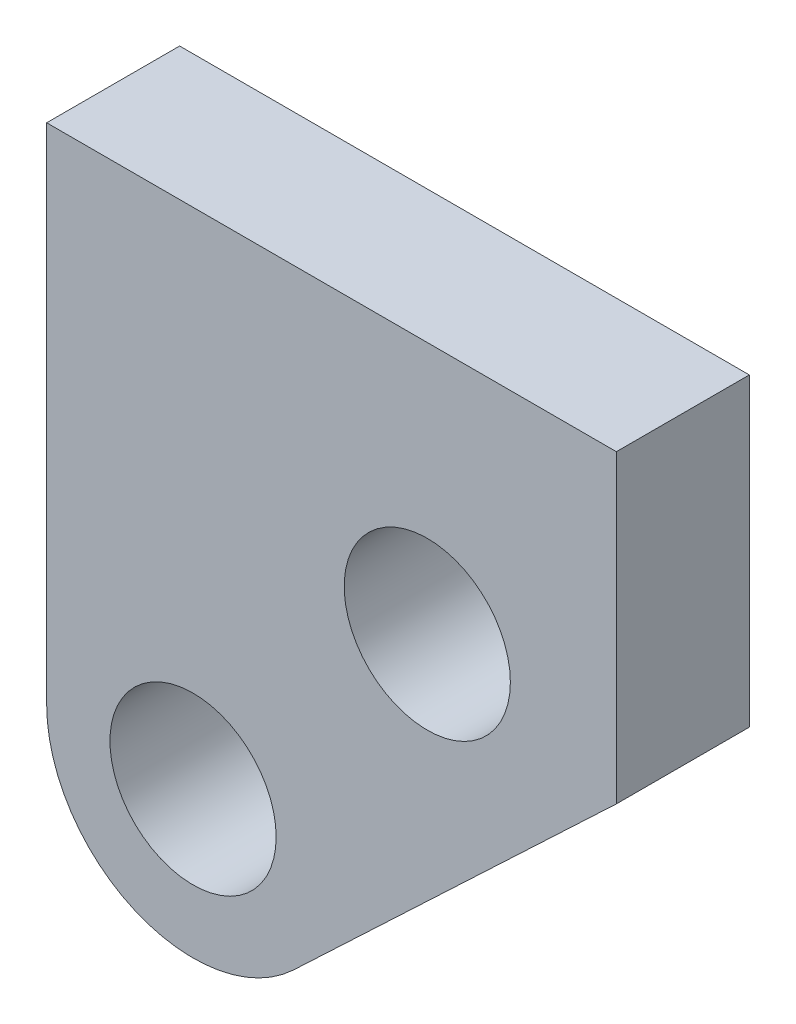
SolidWorks part; units mm, degrees
ref_plane "Plane1" through (0, 0, 0) normal (0, 0, 1) x (1, 0, 0)
ref_plane "Plane2" through (0, 0, 0) normal (0, 1, 0) x (1, 0, 0)
ref_plane "Plane3" through (0, 0, 0) normal (1, 0, 0) x (0, 0, -1)
other "Configuration Table"
sketch "Sketch1" plane through (0, 0, 0) normal (0, 0, 1) x (1, 0, 0)
  line L0 (29.7852, -23.1872) -> (54.0595, -0.2389)
  line L1 (54.0595, 22.7057) -> (11.2112, 22.7057)
  line L2 (54.0595, 22.7057) -> (54.0595, -0.2389)
  line L4 (11.2112, 22.7057) -> (11.2112, -15.1864)
  circle A0 centre (22.2214, -15.1864) radius 6.25 construction
  circle A1 centre (39.8373, 3.7044) radius 6.25 construction
  circle A2 centre (22.2214, -15.1864) radius 6.25
  circle A3 centre (39.8373, 3.7044) radius 6.25
  arc A4 (11.2112, -15.1864) -> (29.7852, -23.1872) centre (22.2214, -15.1864) ccw
extrude "Base-Extrude" add sketch "Sketch1" against normal blind 10
